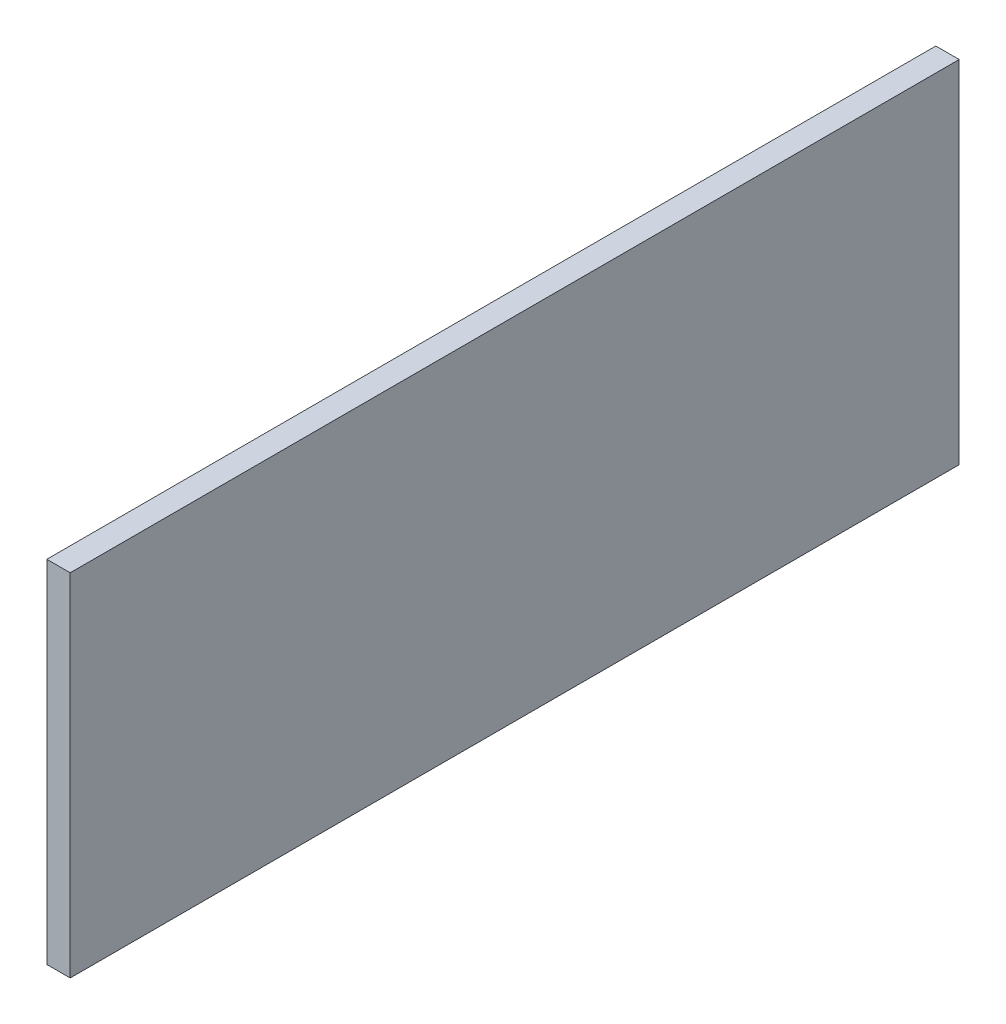
SolidWorks part; units mm, degrees
ref_plane "Front Plane" through (0, 0, 0) normal (0, 0, 1) x (1, 0, 0)
ref_plane "Top Plane" through (0, 0, 0) normal (0, 1, 0) x (1, 0, 0)
ref_plane "Right Plane" through (0, 0, 0) normal (1, 0, 0) x (0, 0, -1)
sketch "Sketch1" plane through (0, 0, 0) normal (1, 0, 0) x (0, 0, -1)
  line L1 (-190, -75) -> (190, -75)
  line L2 (-190, -75) -> (-190, 75)
  line L3 (-190, 75) -> (190, 75)
  line L4 (190, -75) -> (190, 75)
  line L5 (-190, -75) -> (190, 75) construction
  line L6 (-190, 75) -> (190, -75) construction
  point P0 (0, 0)
  dimension "D1" = 380
  dimension "D2" = 150
extrude "Boss-Extrude1" add sketch "Sketch1" along normal blind 10
